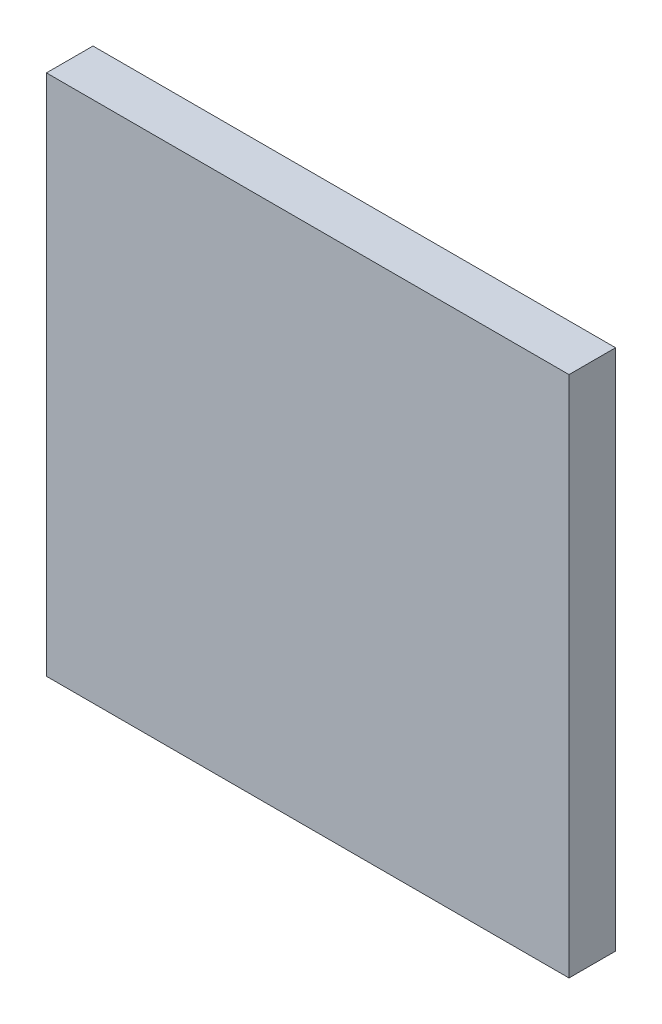
SolidWorks part; units mm, degrees
ref_plane "Front Plane" through (0, 0, 0) normal (0, 0, 1) x (1, 0, 0)
ref_plane "Top Plane" through (0, 0, 0) normal (0, 1, 0) x (1, 0, 0)
ref_plane "Right Plane" through (0, 0, 0) normal (1, 0, 0) x (0, 0, -1)
sketch "Sketch1" plane through (0, 0, 0) normal (0, 0, 1) x (1, 0, 0)
  line L4 (-60.19, -50) -> (-97.69, -50)
  line L5 (-97.69, -50) -> (-97.69, -87.5)
  line L6 (-97.69, -87.5) -> (-60.19, -87.5)
  line L7 (-60.19, -87.5) -> (-60.19, -50)
  line L8 (-60.19, -50) -> (-97.69, -50)
  line L9 (-97.69, -50) -> (-97.69, -87.5)
  line L10 (-97.69, -87.5) -> (-60.19, -87.5)
  line L11 (-60.19, -87.5) -> (-60.19, -50)
  dimension "D1" = 0
extrude "Extrude1" add sketch "Sketch1" along normal blind 3.34
